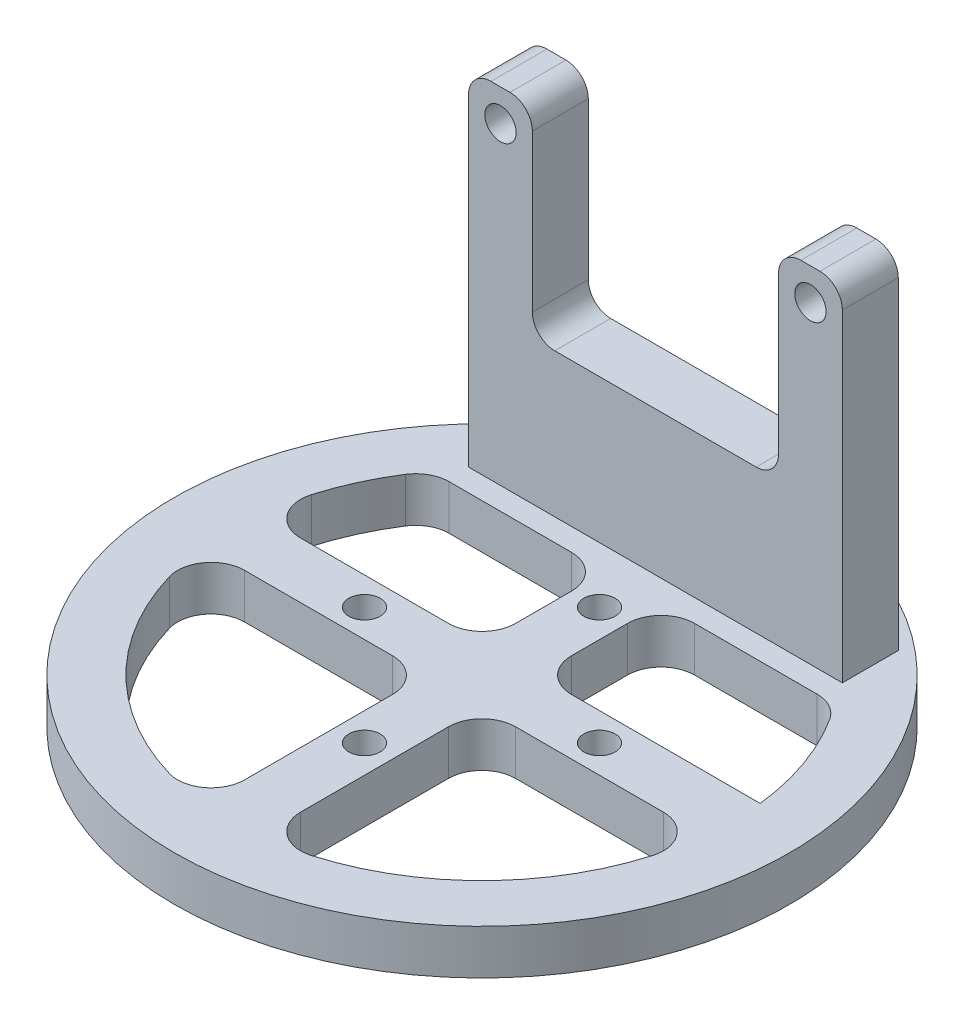
SolidWorks part; units mm, degrees
ref_plane "Front Plane" through (0, 0, 0) normal (0, 0, 1) x (1, 0, 0)
ref_plane "Top Plane" through (0, 0, 0) normal (0, 1, 0) x (1, 0, 0)
ref_plane "Right Plane" through (0, 0, 0) normal (1, 0, 0) x (0, 0, -1)
sketch "Sketch1" plane through (0, 0, 0) normal (0, 0, 1) x (1, 0, 0)
  line L0 (-16.7, 0) -> (16.7, 0)
  line L1 (16.7, 0) -> (16.7, 30.85)
  line L2 (16.7, 30.85) -> (11, 30.85)
  line L3 (11, 30.85) -> (11, 12.85)
  line L4 (11, 12.85) -> (-11, 12.85)
  line L5 (0, 12.85) -> (0, 0) construction
  line L6 (-16.7, 0) -> (-16.7, 30.85)
  line L7 (-16.7, 30.85) -> (-11, 30.85)
  line L8 (-11, 30.85) -> (-11, 12.85)
  circle A0 centre (13.85, 28) radius 1.4
  circle A2 centre (13.85, 28) radius 2.85 construction
  circle A3 centre (-13.85, 28) radius 1.4
  dimension "D3" = 2.8
  dimension "D1" = 28
  dimension "D2" = 13.85
  dimension "D4" = 2.85
  dimension "D5" = 18
extrude "Boss-Extrude1" add sketch "Sketch1" along normal mid plane 5
ref_plane "Plane1" through (0, 0, 18) normal (0, 0, 1) x (1, 0, 0)
sketch "Sketch2" plane through (0, 0, 0) normal (0, 1, 0) x (1, 0, 0)
  line L0 (0, 0) -> (0, -18) construction
  line L1 (-16.9675, -18) -> (16.9675, -18) construction
  line L2 (-18, -4.5) -> (-2.5, -4.5)
  line L3 (-16.7, -2.5) -> (16.7, -2.5) construction
  line L4 (-16.7, -2.5) -> (16.7, -2.5)
  line L5 (2.5, -4.5) -> (2.5, -15.5)
  line L6 (-2.5, -4.5) -> (-2.5, -15.5)
  line L7 (-22.3607, -15.5) -> (-2.5, -15.5)
  line L8 (-22.3607, -20.5) -> (-2.5, -20.5)
  line L9 (0, -18) -> (-27.5, -18) construction
  line L10 (2.5, -15.5) -> (22.3607, -15.5)
  line L11 (-2.5, -20.5) -> (-2.5, -40.3607)
  line L12 (2.5, -20.5) -> (2.5, -40.3607)
  line L13 (2.5, -20.5) -> (22.3607, -20.5)
  line L14 (2.5, -4.5) -> (18, -4.5)
  line L15 (2.5, -20.5) -> (2.5, -15.5) construction
  line L16 (-2.5, -15.5) -> (2.5, -15.5) construction
  circle A0 centre (0, -18) radius 27.5
  arc A1 (-22.3607, -20.5) -> (-2.5, -40.3607) centre (0, -18) ccw construction
  arc A2 (-18, -4.5) -> (-22.3607, -15.5) centre (0, -18) ccw
  arc A3 (-22.3607, -20.5) -> (-2.5, -40.3607) centre (0, -18) ccw
  arc A4 (22.3607, -15.5) -> (-22.3607, -15.5) centre (0, -18) ccw construction
  arc A5 (22.3607, -15.5) -> (18, -4.5) centre (0, -18) ccw
  circle A6 centre (0, -7.5) radius 1.4
  circle A7 centre (0, -18) radius 10.5 construction
  circle A8 centre (10.5, -18) radius 1.4
  circle A9 centre (0, -28.5) radius 1.4
  circle A10 centre (-10.5, -18) radius 1.4
  arc A11 (2.5, -40.3607) -> (22.3607, -20.5) centre (0, -18) ccw construction
  arc A12 (2.5, -40.3607) -> (22.3607, -20.5) centre (0, -18) ccw
  point P26 (0, 0)
  point P27 (0, 0)
  point P28 (0, 0)
  point P35 (0, -18)
  dimension "D1" = 55
  dimension "D2" = 5
  dimension "D5" = 21
  dimension "D6" = 2.8
  dimension "D3" = 2
  dimension "D4" = 5
  dimension "D7" = 4
extrude "Boss-Extrude2" add sketch "Sketch2" against normal blind 4
fillet "Fillet1" radius 3 13 edges at (-2.5, -2, 40.3607) (2.5, -2, 40.3607) (22.3607, -2, 20.5) (2.5, -2, 20.5) (-2.5, -2, 20.5) (-22.3607, -2, 20.5) (-22.3607, -2, 15.5) (-18, -2, 4.5) (-2.5, -2, 15.5) (2.5, -2, 15.5) (18, -2, 4.5) (2.5, -2, 4.5) (-2.5, -2, 4.5)
fillet "Fillet2" radius 2 6 edges at (16.7, 30.85, 0) (11, 12.85, 0) (-11, 12.85, 0) (11, 30.85, 0) (-11, 30.85, 0) (-16.7, 30.85, 0)
